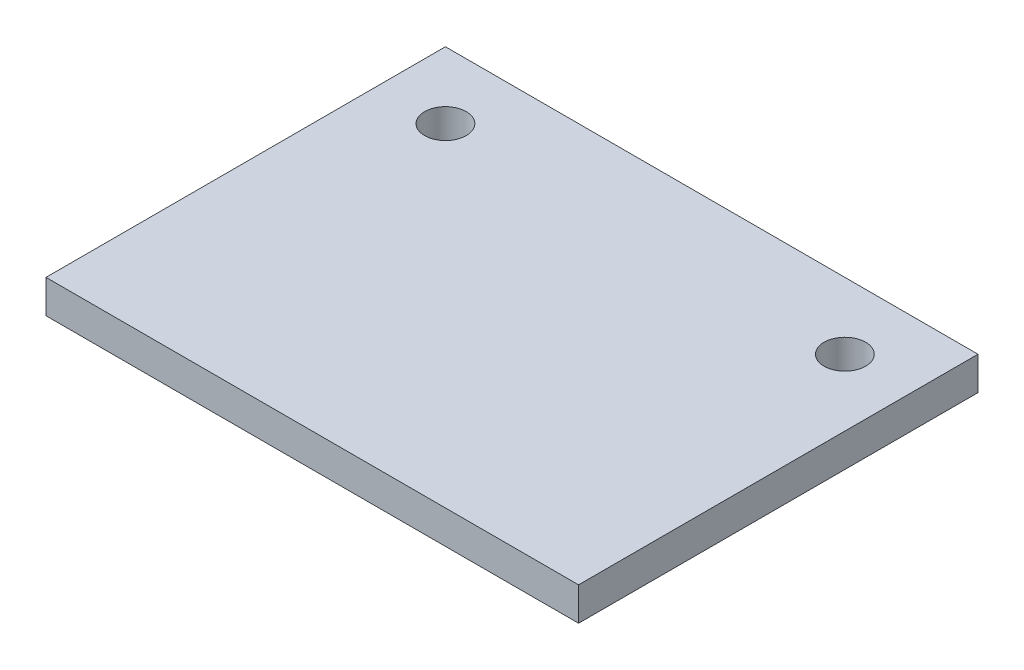
SolidWorks part; units mm, degrees
material "ASTM A36 Steel"
ref_plane "Front Plane" through (0, 0, 0) normal (0, 0, 1) x (1, 0, 0)
ref_plane "Top Plane" through (0, 0, 0) normal (0, 1, 0) x (1, 0, 0)
ref_plane "Right Plane" through (0, 0, 0) normal (1, 0, 0) x (0, 0, -1)
sketch "Sketch1" plane through (0, 0, 0) normal (0, 1, 0) x (1, 0, 0)
  line L1 (64.3902, 63.5122) -> (-95.6098, 63.5122)
  line L2 (64.3902, 63.5122) -> (64.3902, -56.4878)
  line L3 (64.3902, -56.4878) -> (-95.6098, -56.4878)
  line L4 (-95.6098, 63.5122) -> (-95.6098, -56.4878)
  circle A0 centre (44.3902, 43.5122) radius 6.25
  circle A1 centre (-75.6098, 43.5122) radius 6.25
  dimension "D7" = 12.5
  dimension "D8" = 12.5
  dimension "D1" = 160
  dimension "D2" = 120
  dimension "D3" = 20
  dimension "D4" = 20
  dimension "D5" = 20
  dimension "D6" = 20
extrude "Boss-Extrude1" add sketch "Sketch1" along normal blind 10
